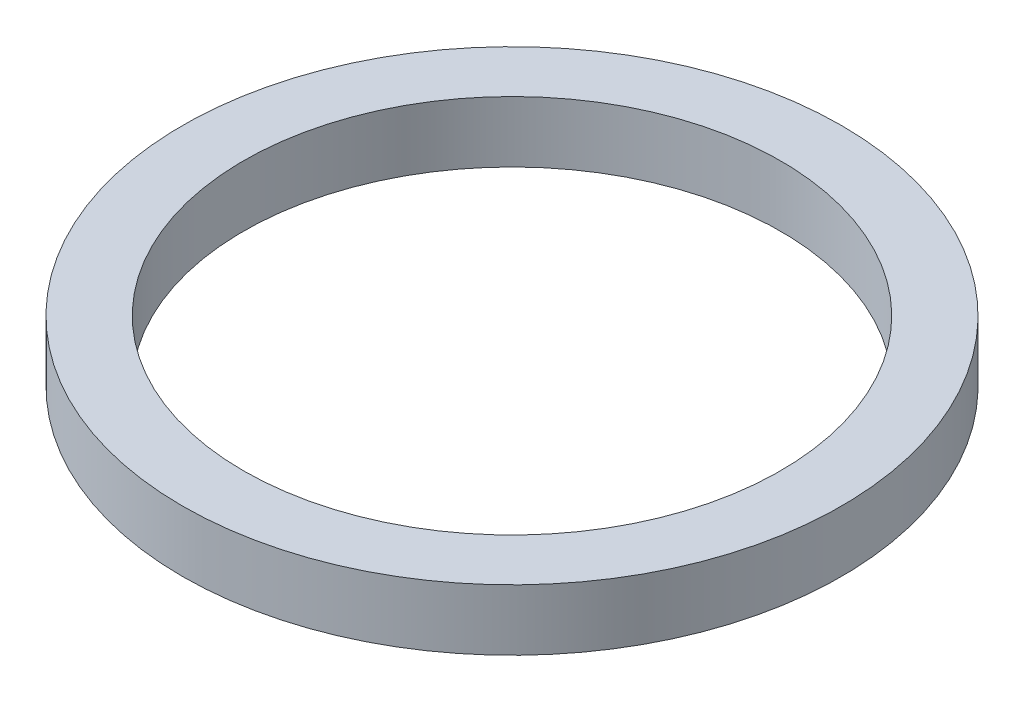
SolidWorks part; units mm, degrees
ref_plane "前基準面" through (0, 0, 0) normal (0, 0, 1) x (1, 0, 0)
ref_plane "上基準面" through (0, 0, 0) normal (0, 1, 0) x (1, 0, 0)
ref_plane "右基準面" through (0, 0, 0) normal (1, 0, 0) x (0, 0, -1)
sketch "草圖1" plane through (0, 0, 0) normal (0, 1, 0) x (1, 0, 0)
  circle A0 centre (0, 0) radius 22
  arc A1 (0.8926, 26.9852) -> (0.8926, -26.9852) centre (0, 0) ccw
  arc A3 (0.8926, -26.9852) -> (0.8926, 26.9852) centre (0, 0) ccw
  dimension "D1" = 44
  dimension "D2" = 5
extrude "填料-伸長1" add sketch "草圖1" along normal mid plane 5 contours A1 A0
